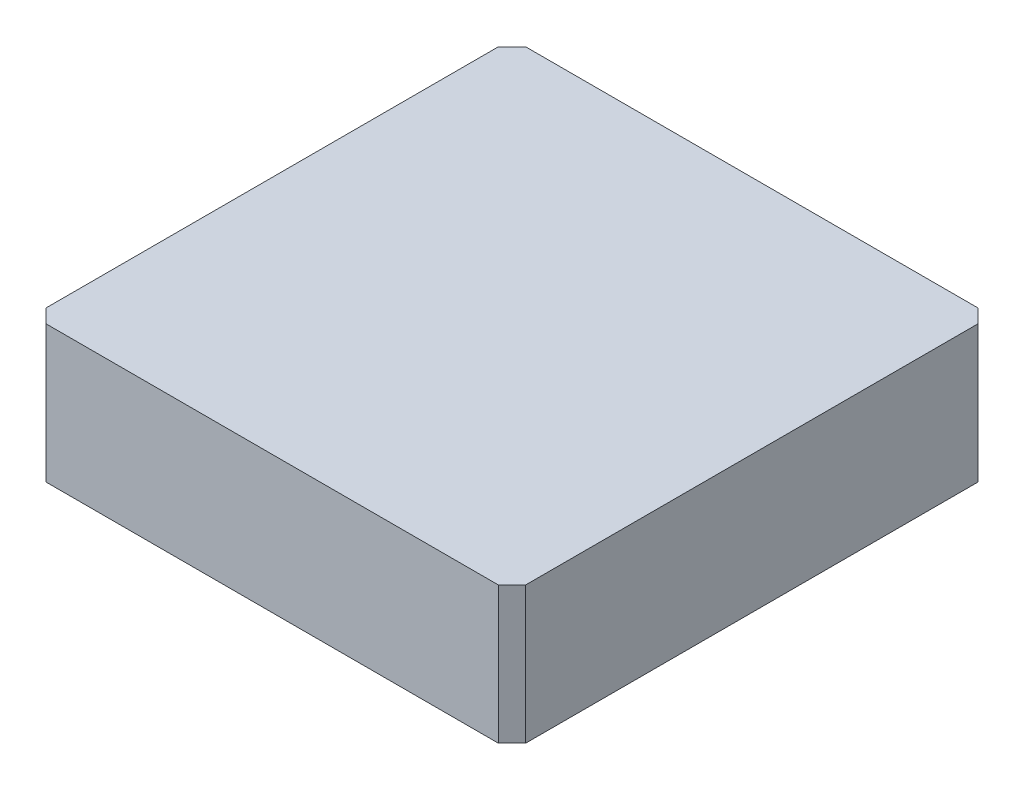
SolidWorks part; units mm, degrees
ref_plane "前视" through (0, 0, 0) normal (0, 0, 1) x (1, 0, 0)
ref_plane "上视" through (0, 0, 0) normal (0, 1, 0) x (1, 0, 0)
ref_plane "右视" through (0, 0, 0) normal (1, 0, 0) x (0, 0, -1)
sketch "草图1" plane through (0, 0, 0) normal (0, 1, 0) x (1, 0, 0)
  line L1 (35, -35) -> (-35, -35)
  line L2 (35, -35) -> (35, 35)
  line L3 (35, 35) -> (-35, 35)
  line L4 (-35, -35) -> (-35, 35)
  line L5 (35, -35) -> (-35, 35) construction
  line L6 (35, 35) -> (-35, -35) construction
  point P0 (0, 0)
  dimension "D1" = 70
  dimension "D2" = 70
extrude "凸台-拉伸1" add sketch "草图1" along normal blind 20
chamfer "倒角1" distance 2 angle 45 4 edges at (-35, 10, 35) (-35, 10, -35) (35, 10, -35) (35, 10, 35)
